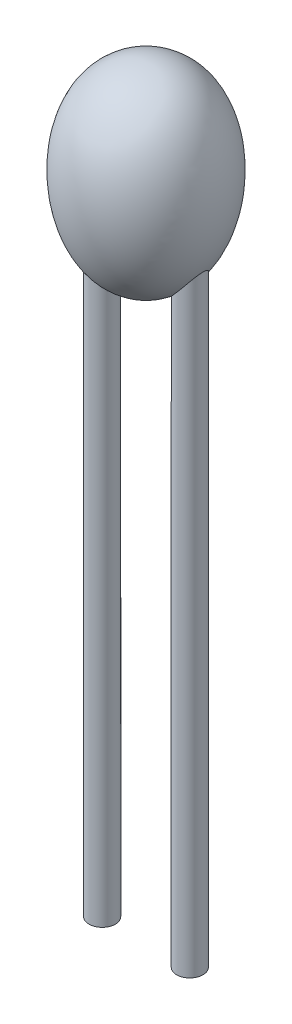
SolidWorks part; units mm, degrees
ref_plane "Front Plane" through (0, 0, 0) normal (0, 0, 1) x (1, 0, 0)
ref_plane "Top Plane" through (0, 0, 0) normal (0, 1, 0) x (1, 0, 0)
ref_plane "Right Plane" through (0, 0, 0) normal (1, 0, 0) x (0, 0, -1)
sketch "Sketch1" plane through (0, 0, 0) normal (0, 0, 1) x (1, 0, 0)
  line L1 (0, 2.0896) -> (0, 0)
  line L2 (0, 0) -> (0.3713, 0)
  line L3 (0.8, 3.6168) -> (0.8, 0.1862) construction
  line L4 (0, 2.0896) -> (0, -10.6029) construction
  spline S0 degree 3 poles (0, 2.0896) (0.9717, 2.0765) (1.0115, 0.453) (0.3713, 0) knots 0 0 0 0 1 1 1 1
revolve "Revolve1" add sketch "Sketch1" angle 360 about L4
sketch "Sketch2" plane through (0, 0, 0) normal (0, -1, 0) x (1, 0, 0)
  line L0 (0, 1.8017) -> (0, -1.942) construction
  circle A0 centre (0.5, 0) radius 0.15
  circle A1 centre (-0.5, 0) radius 0.15
  dimension "D1" = 0.3
  dimension "D2" = 1
extrude "Boss-Extrude1" add sketch "Sketch2" along normal blind 6.6 and the other way blind 1
